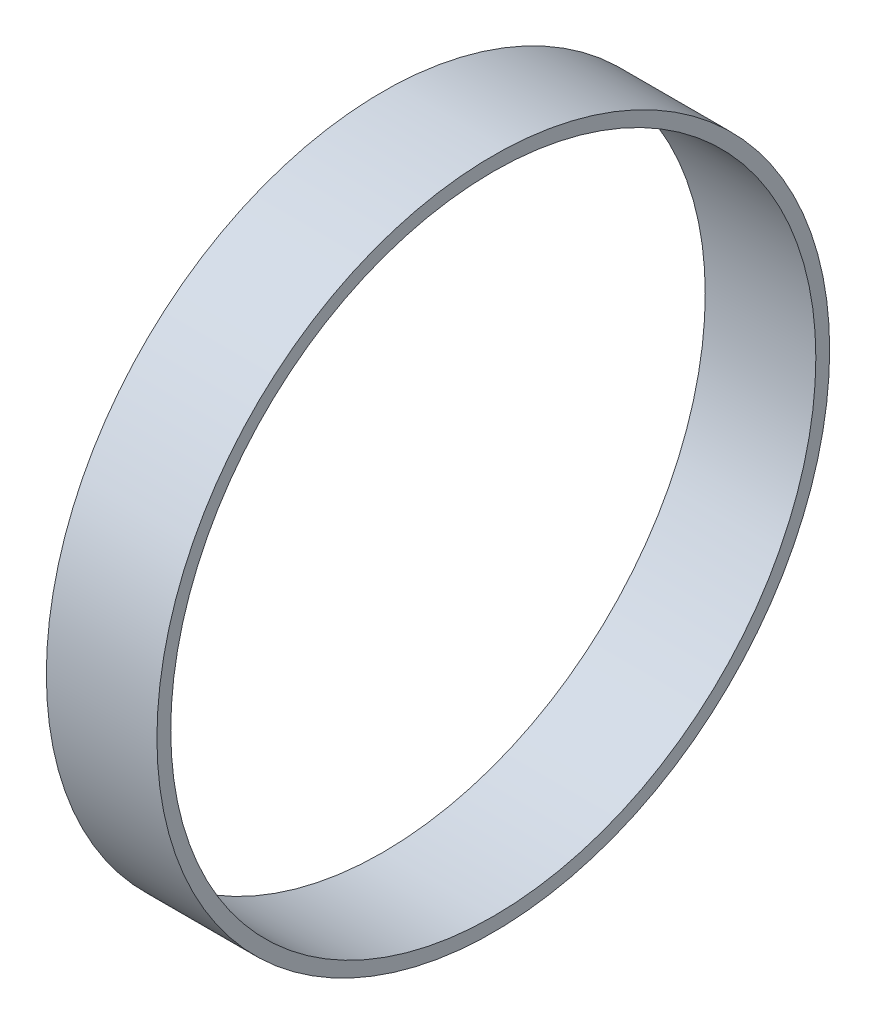
SolidWorks part; units mm, degrees
material "6061 Alloy"
ref_plane "Front Plane" through (0, 0, 0) normal (0, 0, 1) x (1, 0, 0)
ref_plane "Top Plane" through (0, 0, 0) normal (0, 1, 0) x (1, 0, 0)
ref_plane "Right Plane" through (0, 0, 0) normal (1, 0, 0) x (0, 0, -1)
sketch "Sketch1" plane through (0, 0, 0) normal (1, 0, 0) x (0, 0, -1)
  circle A0 centre (-28.5429, 22.1154) radius 35
  circle A2 centre (-28.5429, 22.1154) radius 36.5
  dimension "D1" = 70
  dimension "D2" = 73
extrude "Boss-Extrude1" add sketch "Sketch1" along normal blind 12
